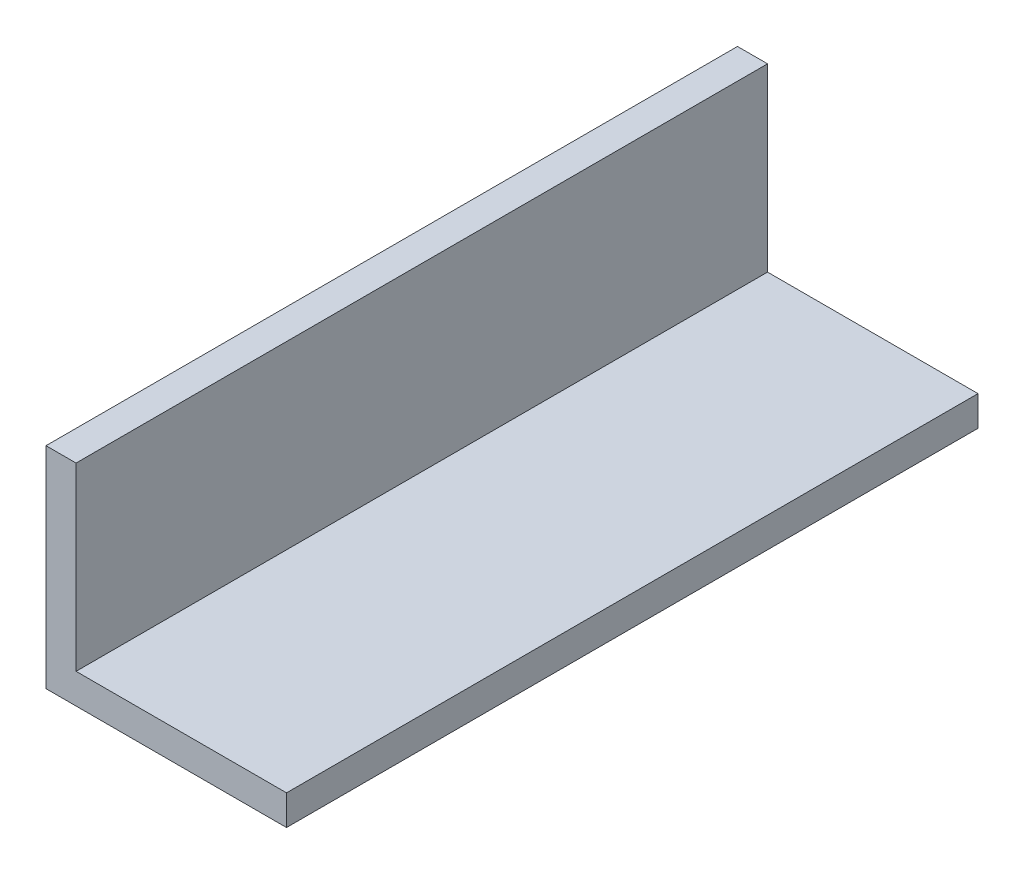
SolidWorks part; units mm, degrees
ref_plane "Plan de face" through (0, 0, 0) normal (1, 0, 0) x (0, 1, 0)
ref_plane "Plan de dessus" through (0, 0, 0) normal (0, 0, 1) x (0, 1, 0)
ref_plane "Plan de droite" through (0, 0, 0) normal (0, 1, 0) x (-1, 0, 0)
sketch "Esquisse2" plane through (0, 0, 0) normal (0, 0, 1) x (0, 1, 0)
  line L0 (0, 35) -> (30, 35)
  line L5 (0, 0) -> (-5, 0)
  line L8 (-5, 0) -> (-5, 35)
  line L10 (-5, 35) -> (-5, 40)
  line L11 (-5, 40) -> (30, 40)
  line L12 (30, 35) -> (30, 40)
  line L13 (0, 35) -> (0, 5)
  line L14 (0, 0) -> (0, 5)
  point P9 (0, 5)
  dimension "D2" = 5
  dimension "D3" = 30
extrude "Boss.-Extru.1" add sketch "Esquisse2" along normal blind 115
